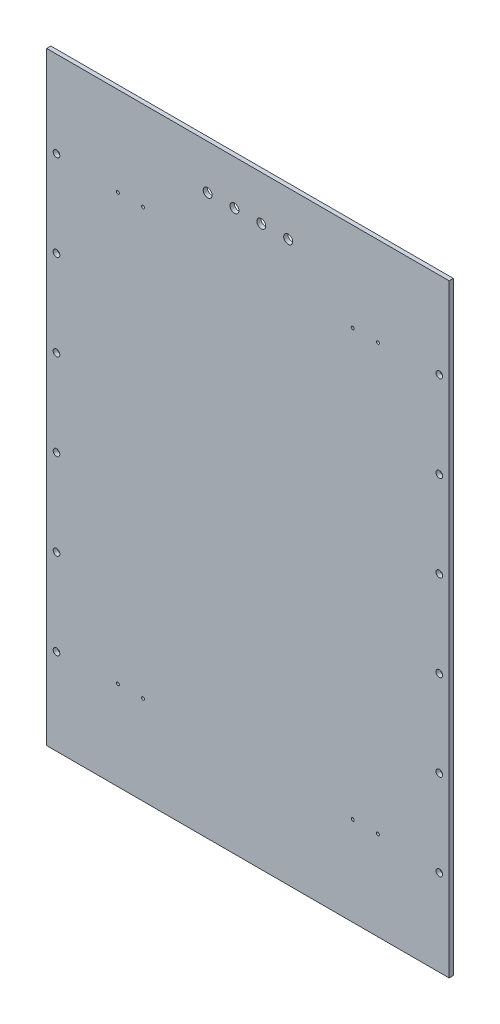
SolidWorks part; units mm, degrees
material "Plain Carbon Steel"
ref_plane "Front Plane" through (0, 0, 0) normal (0, 0, 1) x (1, 0, 0)
ref_plane "Top Plane" through (0, 0, 0) normal (0, 1, 0) x (1, 0, 0)
ref_plane "Right Plane" through (0, 0, 0) normal (1, 0, 0) x (0, 0, -1)
sketch "Sketch1" plane through (0, 0, 0) normal (0, 0, 1) x (1, 0, 0)
  line L1 (-304.8, -457.2) -> (304.8, -457.2)
  line L2 (-304.8, -457.2) -> (-304.8, 457.2)
  line L3 (-304.8, 457.2) -> (304.8, 457.2)
  line L4 (304.8, -457.2) -> (304.8, 457.2)
  line L5 (-304.8, -457.2) -> (304.8, 457.2) construction
  line L6 (-304.8, 457.2) -> (304.8, -457.2) construction
  point P0 (0, 0)
  dimension "D1" = 914.4
  dimension "D2" = 609.6
extrude "Boss-Extrude1" add sketch "Sketch1" along normal mid plane 6.35
sketch "Sketch2" plane through (0, 0, 3.175) normal (0, 0, 1) x (1, 0, 0)
  line L0 (-304.8, -457.2) -> (304.8, -457.2) construction
  line L1 (-304.8, 457.2) -> (-304.8, -457.2) construction
  line L2 (0, 457.2) -> (0, -457.2) construction
  line L3 (304.8, 457.2) -> (-304.8, 457.2) construction
  line L4 (304.8, 0) -> (-304.8, 0) construction
  line L5 (304.8, -457.2) -> (304.8, 457.2) construction
  point P0 (-196.85, -322.2625)
  point P1 (-158.75, -322.2625)
  point P14 (196.85, -322.2625)
  point P15 (158.75, -322.2625)
  point P16 (158.75, 322.2625)
  point P17 (196.85, 322.2625)
  point P18 (-158.75, 322.2625)
  point P19 (-196.85, 322.2625)
  dimension "D1" = 134.9375
  dimension "D2" = 107.95
  dimension "D3" = 38.1
hole_wizard "#8 Clearance Hole1" positions "Sketch2" profile "Sketch3" hole size "#8" standard "ANSI Inch" end condition up to next
sketch "Sketch3" plane through (-196.85, -322.2625, 3.175) normal (1, 0, 0) x (0, -1, 0)
  line L0 (0, 0) -> (0, 6.35)
  line L1 (0, 6.35) -> (2.2479, 6.35)
  line L2 (2.2479, 6.35) -> (2.2479, 0)
  line L5 (2.2479, 0) -> (0, 0)
  line L11 (0, -6.35) -> (0, 107.95) construction
  dimension "Thru Hole Dia." = 4.4958
  dimension "Thru Hole Depth" = 6.35
sketch "Sketch4" plane through (0, 0, 3.175) normal (0, 0, 1) x (1, 0, 0)
  circle A0 centre (60.96, 389.8926) radius 6.7462
  circle A1 centre (60.96, 389.8926) radius 6.7462 construction
  circle A2 centre (-20.32, 389.8926) radius 6.7462 construction
  circle A3 centre (20.32, 389.8926) radius 6.7462 construction
  circle A4 centre (-60.96, 389.8926) radius 6.7462 construction
  circle A5 centre (-20.32, 389.8926) radius 6.7462
  circle A6 centre (20.32, 389.8926) radius 6.7462
  circle A7 centre (-60.96, 389.8926) radius 6.7462
extrude "Cut-Extrude1" cut sketch "Sketch4" against normal through all both and the other way through all
sketch "Sketch8" plane through (0, 0, 3.175) normal (0, 0, 1) x (1, 0, 0)
  line L0 (-304.8, 457.2) -> (-304.8, -457.2) construction
  line L1 (-304.8, -457.2) -> (304.8, -457.2) construction
  line L2 (0, 457.2) -> (0, -457.2) construction
  line L3 (304.8, 457.2) -> (-304.8, 457.2) construction
  circle A0 centre (158.75, -322.2625) radius 2.2479 construction
  point P0 (-289.8775, -326.5714)
  point P7 (-289.8775, -195.9429)
  point P8 (-289.8775, -65.3143)
  point P9 (-289.8775, 65.3143)
  point P10 (-289.8775, 195.9429)
  point P11 (-289.8775, 326.5714)
  point P17 (289.8775, 326.5714)
  point P18 (289.8775, 195.9429)
  point P19 (289.8775, 65.3143)
  point P20 (289.8775, -65.3143)
  point P21 (289.8775, -195.9429)
  point P22 (289.8775, -326.5714)
  dimension "D1" = 14.9225
  dimension "D2" = 130.6286
  dimension "D4" = 126.3196
  dimension "D3" = 6
hole_wizard "3/8 Clearance Hole1" positions "Sketch8" profile "Sketch9" hole size "3/8" standard "ANSI Inch" end condition up to next
sketch "Sketch9" plane through (-289.8775, -326.5714, 3.175) normal (1, 0, 0) x (0, -1, 0)
  line L0 (0, 0) -> (0, 6.35)
  line L1 (0, 6.35) -> (5.0419, 6.35)
  line L2 (5.0419, 6.35) -> (5.0419, 0)
  line L5 (5.0419, 0) -> (0, 0)
  line L11 (0, -6.35) -> (0, 107.95) construction
  dimension "Thru Hole Dia." = 10.0838
  dimension "Thru Hole Depth" = 6.35
